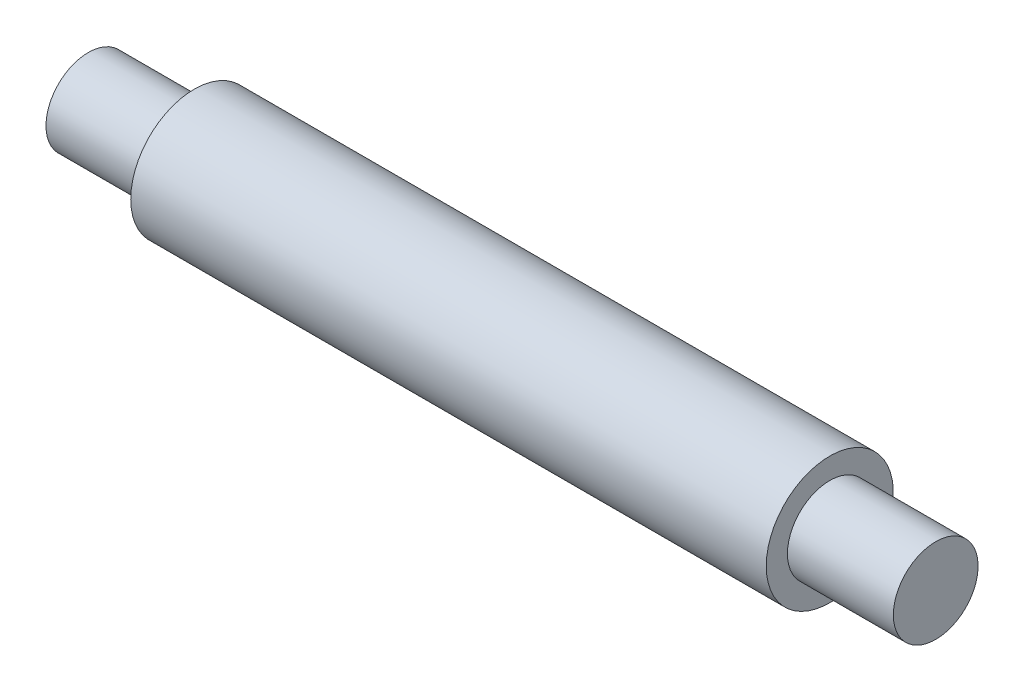
SolidWorks part; units mm, degrees
ref_plane "Front Plane" through (0, 0, 0) normal (0, 0, 1) x (1, 0, 0)
ref_plane "Top Plane" through (0, 0, 0) normal (0, 1, 0) x (1, 0, 0)
ref_plane "Right Plane" through (0, 0, 0) normal (1, 0, 0) x (0, 0, -1)
sketch "Sketch1" plane through (0, 0, 0) normal (0, 0, 1) x (1, 0, 0)
  line L0 (0, 0) -> (80, 0)
  line L1 (0, 0) -> (0, 4)
  line L2 (0, 4) -> (10, 4)
  line L3 (10, 4) -> (10, 6)
  line L4 (10, 6) -> (70, 6)
  line L5 (70, 6) -> (70, 4)
  line L6 (70, 4) -> (80, 4)
  line L7 (80, 4) -> (80, 0)
revolve "Revolve1" add sketch "Sketch1" angle 360 about L0
